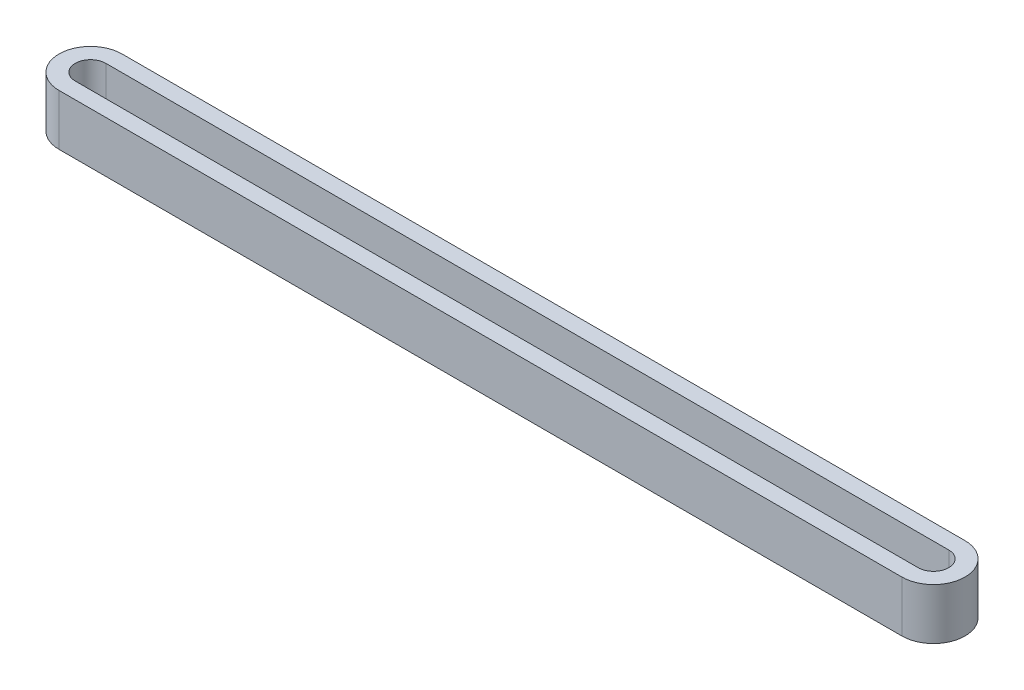
SolidWorks part; units mm, degrees
material "Natural Rubber"
ref_plane "Front Plane" through (0, 0, 0) normal (0, 0, 1) x (1, 0, 0)
ref_plane "Top Plane" through (0, 0, 0) normal (0, 1, 0) x (1, 0, 0)
ref_plane "Right Plane" through (0, 0, 0) normal (1, 0, 0) x (0, 0, -1)
sketch "Sketch1" plane through (0, 0, 0) normal (0, 1, 0) x (1, 0, 0)
  line L0 (82.5, -6.175) -> (-82.5, -6.175)
  line L1 (82.5, -3) -> (-82.5, -3)
  line L3 (82.5, 3) -> (-82.5, 3)
  line L5 (82.5, -3) -> (-82.5, 3) construction
  line L6 (82.5, 3) -> (-82.5, -3) construction
  line L7 (82.5, 6.175) -> (-82.5, 6.175)
  arc A0 (-82.5, 3) -> (-82.5, -3) centre (-82.5, 0) ccw
  arc A1 (82.5, 3) -> (82.5, -3) centre (82.5, 0) cw
  arc A2 (-82.5, 6.175) -> (-82.5, -6.175) centre (-82.5, 0) ccw
  arc A3 (82.5, 6.175) -> (82.5, -6.175) centre (82.5, 0) cw
  point P0 (0, 0)
  dimension "D3" = 3.175
  dimension "D1" = 6
  dimension "D2" = 165
extrude "Boss-Extrude1" add sketch "Sketch1" along normal blind 10
other "Flex3" [suppressed] parameters "D0"=50, "D1"=0, "D2"=0
